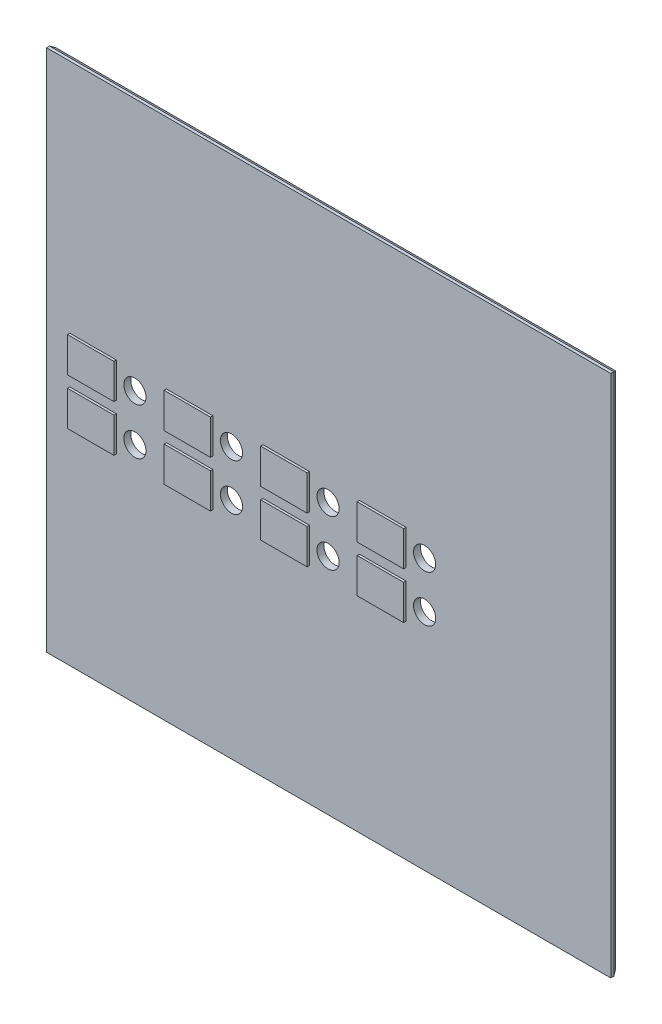
SolidWorks part; units mm, degrees
ref_plane "Plano frontal" through (0, 0, 0) normal (0, 0, 1) x (1, 0, 0)
ref_plane "Plano superior" through (0, 0, 0) normal (0, 1, 0) x (1, 0, 0)
ref_plane "Plano direito" through (0, 0, 0) normal (1, 0, 0) x (0, 0, -1)
sketch "Esboço1" plane through (0, 0, 0) normal (0, 0, 1) x (1, 0, 0)
  line L1 (-242.5, -225) -> (242.5, -225)
  line L2 (-242.5, -225) -> (-242.5, 225)
  line L3 (-242.5, 225) -> (242.5, 225)
  line L4 (242.5, -225) -> (242.5, 225)
extrude "Ressalto-extrusão1" add sketch "Esboço1" along normal blind 6
sketch "Esboço2" plane through (0, 0, 6) normal (0, 0, 1) x (1, 0, 0)
  line L0 (-222.5, -1019.0299) -> (-222.5, 48980.9701) construction
  line L1 (-828.6384, -7.5) -> (49171.3616, -7.5) construction
  line L2 (-828.6384, -30) -> (49171.3616, -30) construction
  line L3 (-182.5, -1019.0299) -> (-182.5, 48980.9701) construction
  line L4 (-828.6384, -67.5) -> (49171.3616, -67.5) construction
  line L5 (-828.6384, 22.5) -> (49171.3616, 22.5) construction
  line L6 (-828.6384, -105) -> (49171.3616, -105) construction
  line L7 (-177.5, -1019.0299) -> (-177.5, 48980.9701) construction
  line L8 (-828.6384, 45) -> (49171.3616, 45) construction
  line L9 (-155.5, -1019.0299) -> (-155.5, 48980.9701) construction
  line L11 (-222.5, 22.5) -> (-182.5564, 22.5)
  line L12 (-222.5, 22.5) -> (-222.5, -7.5)
  line L13 (-222.5, -7.5) -> (-182.5564, -7.5)
  line L14 (-182.5564, 22.5) -> (-182.5564, -7.5)
extrude "Ressalto-extrusão2" add sketch "Esboço2" along normal blind 2
pattern_linear "Padrão linear1" count 4 spacing 83 along (1, 0, 0) count 2 spacing 40 along (0, -1, 0) of "Ressalto-extrusão2"
sketch "Esboço3" plane through (0, 0, 6) normal (0, 0, 1) x (1, 0, 0)
  circle A0 centre (-166.5564, 7.5) radius 9.525
  point P1 (0, 0)
  point P3 (-166.5564, 7.5)
extrude "Corte-extrusão1" cut sketch "Esboço3" against normal through all contours A0
pattern_linear "Padrão linear2" count 4 spacing 83 along (1, 0, 0) count 2 spacing 40 along (0, -1, 0) of "Corte-extrusão1"
chamfer "Chanfro1" distance 2 angle 60 4 edges at (0, -225, 0) (242.5, 0, 0) (0, 225, 0) (-242.5, 0, 0)
